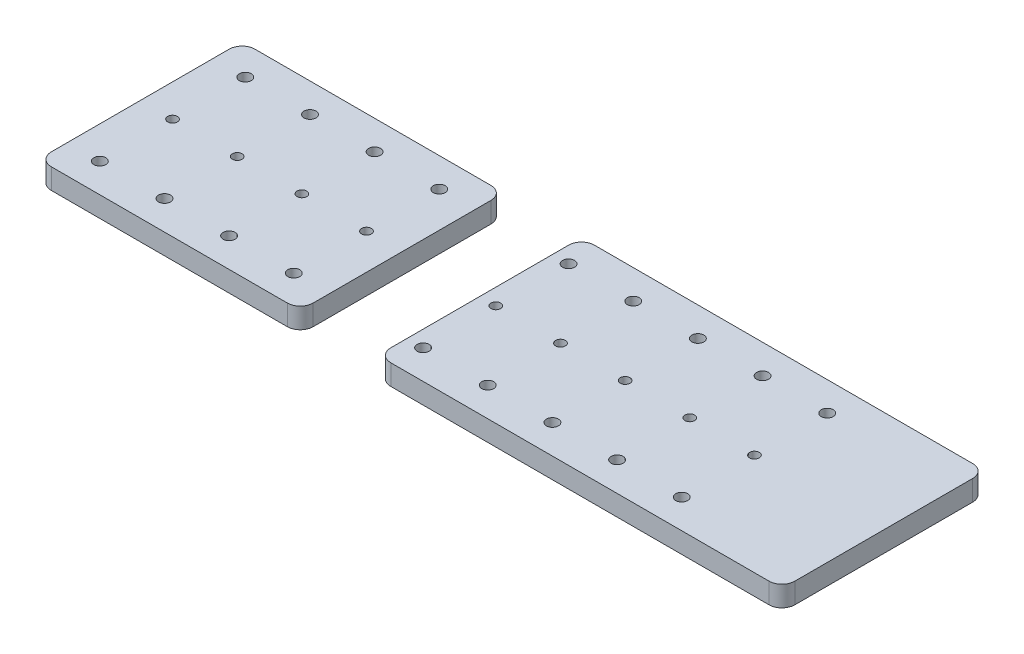
SolidWorks part; units mm, degrees
material "Balsa"
ref_plane "Front Plane" through (0, 0, 0) normal (0, 0, 1) x (1, 0, 0)
ref_plane "Top Plane" through (0, 0, 0) normal (0, 1, 0) x (1, 0, 0)
ref_plane "Right Plane" through (0, 0, 0) normal (1, 0, 0) x (0, 0, -1)
sketch "Sketch1" plane through (0, 0, 0) normal (0, 1, 0) x (1, 0, 0)
  line L0 (0, 0) -> (10, 0) construction
  line L1 (10, 0) -> (10, 22.5) construction
  line L2 (10, 22.5) -> (30, 22.5) construction
  line L3 (0, 0) -> (0, 31.5)
  line L4 (0, 31.5) -> (230, 31.5)
  line L5 (230, 31.5) -> (230, -31.5)
  line L6 (230, -31.5) -> (0, -31.5)
  line L7 (0, -31.5) -> (0, 0)
  circle A0 centre (10, 22.5) radius 1.85
  circle A1 centre (30, 22.5) radius 1.85
  circle A2 centre (50, 22.5) radius 1.85
  circle A3 centre (70, 22.5) radius 1.85
  circle A4 centre (90, 22.5) radius 1.85
  circle A5 centre (110, 22.5) radius 1.85
  circle A6 centre (130, 22.5) radius 1.85
  circle A7 centre (150, 22.5) radius 1.85
  circle A8 centre (170, 22.5) radius 1.85
  circle A9 centre (10, 0) radius 1.5
  circle A10 centre (30, 0) radius 1.5
  circle A11 centre (50, 0) radius 1.5
  circle A12 centre (70, 0) radius 1.5
  circle A13 centre (90, 0) radius 1.5
  circle A14 centre (110, 0) radius 1.5
  circle A15 centre (170, -22.5) radius 1.85
  circle A16 centre (150, -22.5) radius 1.85
  circle A17 centre (130, -22.5) radius 1.85
  circle A18 centre (110, -22.5) radius 1.85
  circle A19 centre (90, -22.5) radius 1.85
  circle A20 centre (70, -22.5) radius 1.85
  circle A21 centre (50, -22.5) radius 1.85
  circle A22 centre (30, -22.5) radius 1.85
  circle A23 centre (10, -22.5) radius 1.85
  circle A24 centre (130, 0) radius 1.5
  circle A25 centre (150, 0) radius 1.5
  circle A26 centre (170, 0) radius 1.5
  circle A27 centre (190, 22.5) radius 1.85
  circle A28 centre (190, -22.5) radius 1.85
  circle A29 centre (190, 0) radius 1.5
  dimension "D3" = 3.7
  dimension "D5" = 20
  dimension "D8" = 3
  dimension "D1" = 45
  dimension "D2" = 10
  dimension "D6" = 230
  dimension "D7" = 63
  dimension "D4" = 10
  dimension "D9" = 10
extrude "Boss-Extrude1" add sketch "Sketch1" along normal blind 6.35
sketch "Sketch3" plane through (0, 6.35, 0) normal (0, 1, 0) x (1, 0, 0)
  line L0 (230, 31.5) -> (0, 31.5) construction
  line L1 (105, 31.5) -> (81, 31.5)
  line L2 (105, 31.5) -> (105, -31.5)
  line L3 (105, -31.5) -> (81, -31.5)
  line L4 (81, 31.5) -> (81, -31.5)
  line L5 (0, -31.5) -> (230, -31.5) construction
  circle A1 centre (90, 22.5) radius 1.85 construction
  dimension "D2" = 15
  dimension "D1" = 9
extrude "Cut-Extrude1" cut sketch "Sketch3" against normal through all
fillet "Fillet1" radius 4 4 edges at (0, 3.175, 31.5) (0, 3.175, -31.5) (81, 3.175, 31.5) (81, 3.175, -31.5)
fillet "Fillet2" radius 4 4 edges at (230, 3.175, 31.5) (230, 3.175, -31.5) (105, 3.175, 31.5) (105, 3.175, -31.5)
